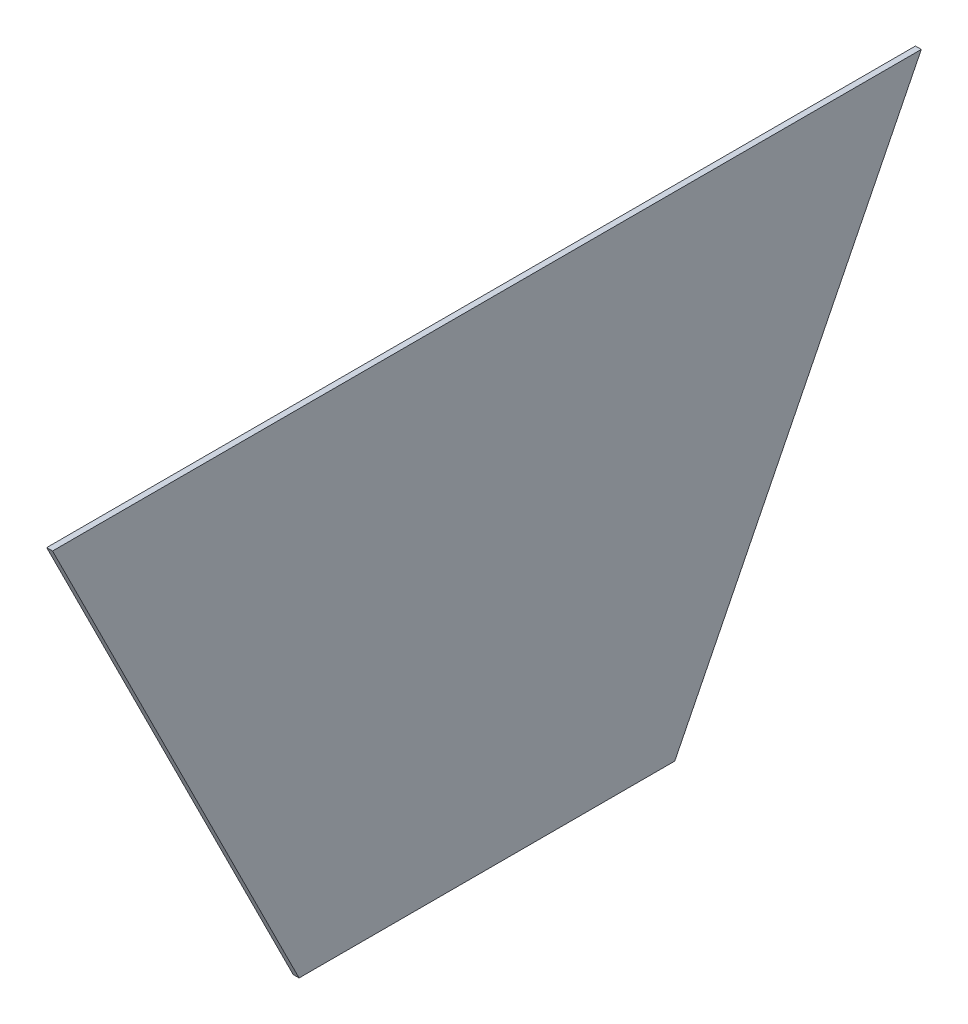
SolidWorks part; units mm, degrees
material "Acrylic (Medium-high impact)"
ref_plane "Front Plane" through (0, 0, 0) normal (0, 0, 1) x (1, 0, 0)
ref_plane "Top Plane" through (0, 0, 0) normal (0, 1, 0) x (1, 0, 0)
ref_plane "Right Plane" through (0, 0, 0) normal (1, 0, 0) x (0, 0, -1)
sketch "Sketch1" plane through (0, 0, 0) normal (1, 0, 0) x (0, 0, -1)
  line L0 (0, 0) -> (101.6, 0)
  line L1 (101.6, 0) -> (234.95, 266.7)
  line L2 (234.95, 266.7) -> (-234.95, 266.7)
  line L3 (0, 0) -> (-101.6, 0)
  line L4 (-101.6, 0) -> (-234.95, 266.7)
  point P3 (0, 266.7)
  dimension "D1" = 101.6
  dimension "D2" = 101.6
  dimension "D3" = 469.9
  dimension "D4" = 266.7
extrude "Boss-Extrude1" add sketch "Sketch1" along normal blind 3.175
